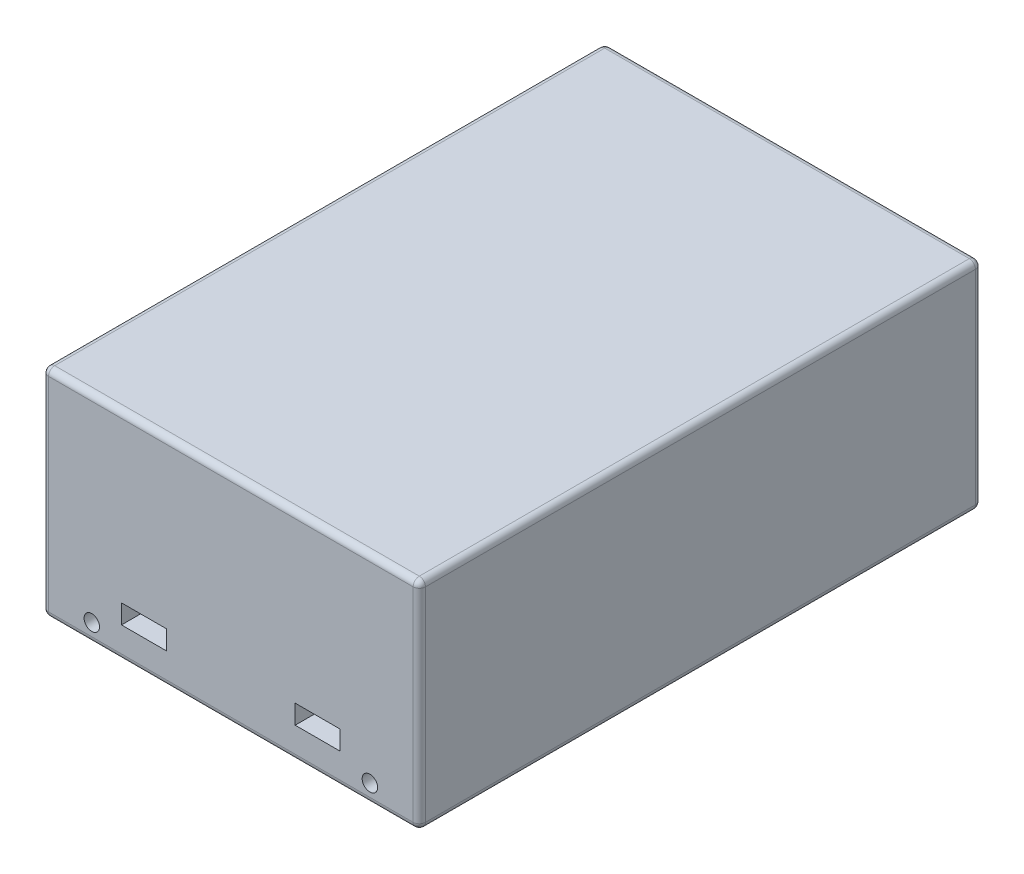
SolidWorks part; units mm, degrees
ref_plane "前视基准面" through (0, 0, 0) normal (0, 0, 1) x (1, 0, 0)
ref_plane "上视基准面" through (0, 0, 0) normal (0, 1, 0) x (1, 0, 0)
ref_plane "右视基准面" through (0, 0, 0) normal (1, 0, 0) x (0, 0, -1)
sketch "草图1" plane through (0, 0, 0) normal (0, 1, 0) x (1, 0, 0)
  line L1 (-30.5, 45.5) -> (30.5, 45.5)
  line L2 (-30.5, 45.5) -> (-30.5, -45.5)
  line L3 (-30.5, -45.5) -> (30.5, -45.5)
  line L4 (30.5, 45.5) -> (30.5, -45.5)
  line L5 (-30.5, 45.5) -> (30.5, -45.5) construction
  line L6 (-30.5, -45.5) -> (30.5, 45.5) construction
  point P0 (0, 0)
extrude "凸台-拉伸1" add sketch "草图1" along normal blind 35
sketch "草图2" plane through (0, 0, 45.5) normal (0, 0, 1) x (1, 0, 0)
  line L0 (-30.5, 0) -> (30.5, 0) construction
  line L1 (30.5, 35) -> (30.5, 0) construction
  circle A0 centre (22.5, 3) radius 1.5
  circle A1 centre (-22.5, 3) radius 1.5
  dimension "D1" = 3
  dimension "D2" = 3
  dimension "D3" = 45
  dimension "D4" = 8
hole_wizard "M3 螺纹孔1" positions "3D草图1" profile "草图3" tap size "M3" standard "ISO"
sketch3d "3D草图1"
  point P0 (-22.5, 3, 45.5)
  point P3 (22.5, 3, 45.5)
cosmetic thread "孔螺蚊线3" parameters "D1"=9.98, "D2"=3
cosmetic thread "孔螺蚊线4" parameters "D1"=9.98, "D2"=3
sketch "草图3" plane through (-22.5, 3, 45.5) normal (1, 0, 0) x (0, -1, 0)
  line L0 (0, 0) -> (0, 10.7511)
  line L1 (0, 10.7511) -> (1.25, 10)
  line L2 (1.25, 10) -> (1.25, 0)
  line L5 (1.25, 0) -> (0, 0)
  line L10 (0, 10.7511) -> (-1.25, 10) construction
  line L11 (0, -6.35) -> (0, 107.95) construction
  dimension "螺纹孔钻头直径" = 2.5
  dimension "螺纹孔钻头深度" = 10
  dimension "导头角度" = 118
hole_wizard "M3x0.5 螺纹孔1" positions "草图4" profile "草图5" tap size "M3x0.5" standard "ANSI Metric"
sketch "草图4" plane through (0, 0, -45.5) normal (0, 0, -1) x (-1, 0, 0)
  point P0 (-22.5, 3)
  point P3 (22.5, 3)
sketch "草图5" plane through (22.5, 3, -45.5) normal (1, 0, 0) x (0, 1, 0)
  line L0 (0, 0) -> (0, 10.7511)
  line L1 (0, 10.7511) -> (1.25, 10)
  line L2 (1.25, 10) -> (1.25, 0)
  line L5 (1.25, 0) -> (0, 0)
  line L10 (0, 10.7511) -> (-1.25, 10) construction
  line L11 (0, -6.35) -> (0, 107.95) construction
  dimension "螺纹孔钻头直径" = 2.5
  dimension "螺纹孔钻头深度" = 10
  dimension "导头角度" = 118
cosmetic thread "孔螺蚊线5" parameters "D1"=9.98, "D2"=3
cosmetic thread "孔螺蚊线6" parameters "D1"=9.98, "D2"=3
sketch "草图6" plane through (0, 0, 0) normal (0, -1, 0) x (-1, 0, 0)
  line L0 (30.5, 45.5) -> (30.5, -45.5) construction
  circle A0 centre (14, 0) radius 1.5
  circle A1 centre (-14, 0) radius 1.5
  dimension "D1" = 28
  dimension "D2" = 16.5
hole_wizard "M3 螺纹孔2" positions "草图7" profile "草图8" tap size "M3" standard "ISO"
sketch "草图7" plane through (0, 0, 0) normal (0, -1, 0) x (-1, 0, 0)
  point P0 (14, 0)
  point P3 (-14, 0)
sketch "草图8" plane through (-14, 0, 0) normal (1, 0, 0) x (0, 0, -1)
  line L0 (0, 0) -> (0, 10.7511)
  line L1 (0, 10.7511) -> (1.25, 10)
  line L2 (1.25, 10) -> (1.25, 0)
  line L5 (1.25, 0) -> (0, 0)
  line L10 (0, 10.7511) -> (-1.25, 10) construction
  line L11 (0, -6.35) -> (0, 107.95) construction
  dimension "螺纹孔钻头直径" = 2.5
  dimension "螺纹孔钻头深度" = 10
  dimension "导头角度" = 118
cosmetic thread "孔螺蚊线7" parameters "D1"=9.98, "D2"=3
cosmetic thread "孔螺蚊线8" parameters "D1"=9.98, "D2"=3
fillet "圆角1" radius 1 12 edges at (30.5, 35, 0) (-30.5, 0, 0) (-30.5, 17.5, -45.5) (0, 0, -45.5) (30.5, 17.5, -45.5) (30.5, 0, 0) (0, 0, 45.5) (-30.5, 17.5, 45.5) (30.5, 17.5, 45.5) (0, 35, -45.5) (-30.5, 35, 0) (0, 35, 45.5)
sketch "草图9" plane through (0, 0, 45.5) normal (0, 0, 1) x (1, 0, 0)
  line L0 (0, 34) -> (0, 0) construction
  line L1 (29.5, 34) -> (-29.5, 34) construction
  line L2 (-10.4111, 6.6124) -> (-17.6969, 6.6124) construction
  line L3 (10.4111, 8.1602) -> (17.6969, 8.1602)
  line L4 (10.4111, 8.1602) -> (10.4111, 5.0645)
  line L5 (10.4111, 5.0645) -> (17.6969, 5.0645)
  line L6 (17.6969, 8.1602) -> (17.6969, 5.0645)
  line L7 (14.054, 5.0645) -> (14.054, 8.1602) construction
  line L8 (10.4111, 6.6124) -> (17.6969, 6.6124) construction
  line L9 (-14.054, 5.0645) -> (-14.054, 8.1602) construction
  line L10 (-17.6969, 8.1602) -> (-17.6969, 5.0645)
  line L11 (-10.4111, 5.0645) -> (-17.6969, 5.0645)
  line L12 (-10.4111, 8.1602) -> (-10.4111, 5.0645)
  line L13 (-10.4111, 8.1602) -> (-17.6969, 8.1602)
  point P5 (14.054, 6.6124)
  point P9 (14.0644, 6.6124)
  point P10 (14.054, 5.0645)
  point P19 (-14.054, 6.6124)
extrude "切除-拉伸1" cut sketch "草图9" against normal blind 10
sketch "草图10" plane through (-30.5, 0, 0) normal (-1, 0, 0) x (0, 0, 1)
  line L0 (0, 34) -> (0, 0) construction
  line L1 (44.5, 34) -> (-44.5, 34) construction
  line L3 (-37.7991, 6.7105) -> (37.7991, 6.7105)
  line L4 (-37.7991, 6.7105) -> (-37.7991, 3.2807)
  line L5 (-37.7991, 3.2807) -> (37.7991, 3.2807)
  line L6 (37.7991, 6.7105) -> (37.7991, 3.2807)
  line L7 (0, 3.2807) -> (0, 6.7105) construction
  line L8 (-37.7991, 4.9956) -> (37.7991, 4.9956) construction
  point P5 (0, 4.9956)
extrude "切除-拉伸2" cut sketch "草图10" against normal blind 10
